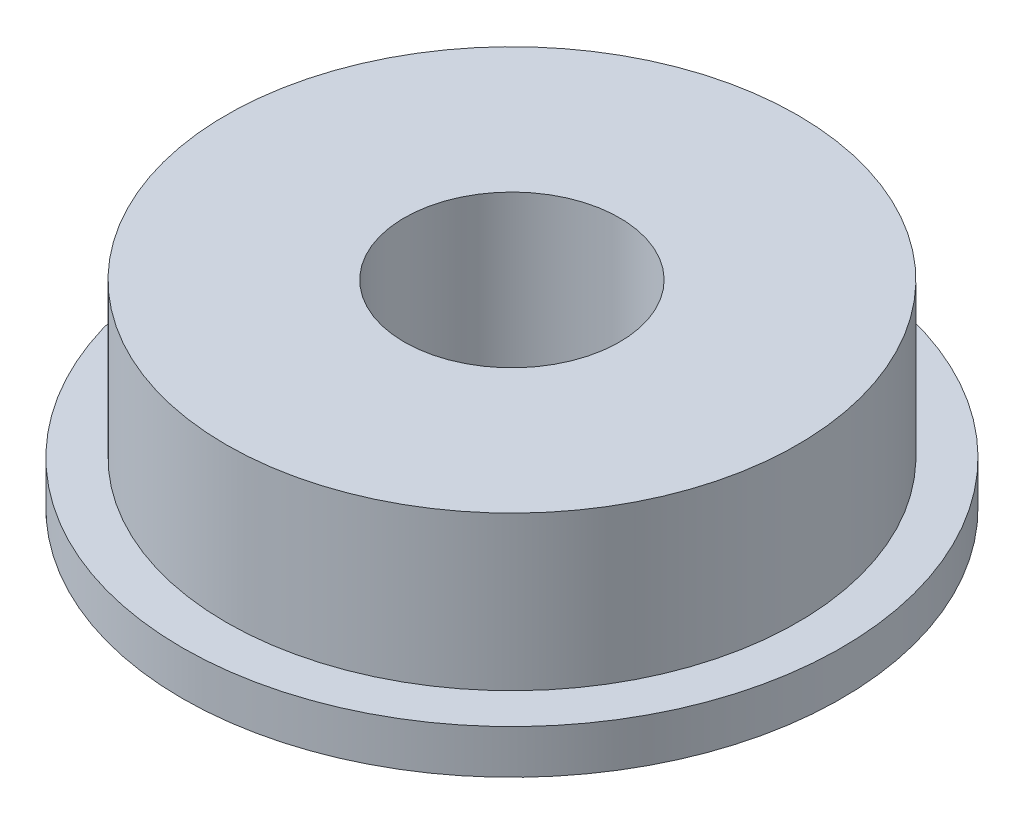
SolidWorks part; units mm, degrees
material "Stainless Steel (ferritic)"
ref_plane "Front Plane" through (0, 0, 0) normal (0, 0, 1) x (1, 0, 0)
ref_plane "Top Plane" through (0, 0, 0) normal (0, 1, 0) x (1, 0, 0)
ref_plane "Right Plane" through (0, 0, 0) normal (1, 0, 0) x (0, 0, -1)
sketch "Sketch1" plane through (0, 0, 0) normal (0, 1, 0) x (1, 0, 0)
  circle A0 centre (0, 0) radius 7.5
  dimension "D1" = 15
extrude "Boss-Extrude1" add sketch "Sketch1" along normal blind 1
sketch "Sketch2" plane through (0, 1, 0) normal (0, 1, 0) x (1, 0, 0)
  circle A0 centre (0, 0) radius 6.5
  dimension "D1" = 13
extrude "Boss-Extrude2" add sketch "Sketch2" along normal blind 3.5
sketch "Sketch3" plane through (0, 4.5, 0) normal (0, 1, 0) x (1, 0, 0)
  circle A0 centre (0, 0) radius 2.45
  dimension "D1" = 4.9
extrude "Cut-Extrude1" cut sketch "Sketch3" against normal up to surface (4.5 mm away) up to face at (0, 0, 7.5)
